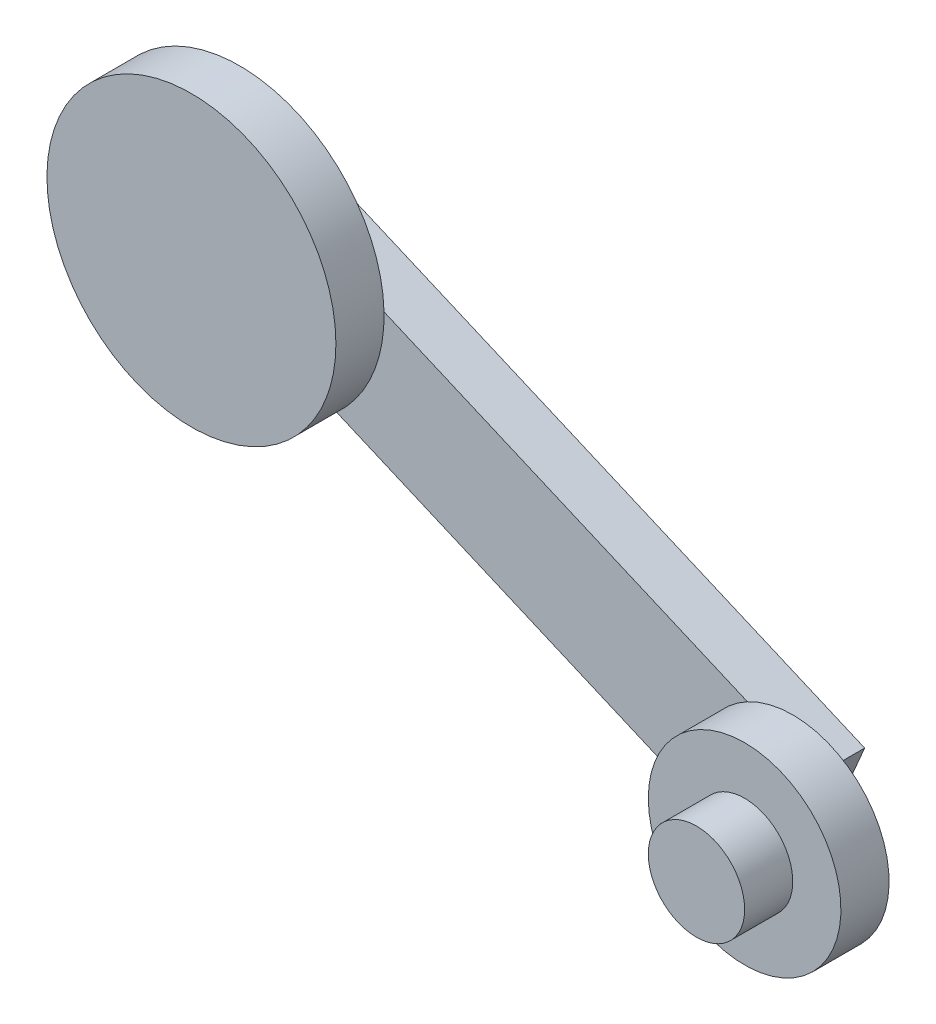
SolidWorks part; units mm, degrees
ref_plane "Front Plane" through (0, 0, 0) normal (0, 0, 1) x (1, 0, 0)
ref_plane "Top Plane" through (0, 0, 0) normal (0, 1, 0) x (1, 0, 0)
ref_plane "Right Plane" through (0, 0, 0) normal (1, 0, 0) x (0, 0, -1)
sketch "Sketch1" plane through (0, 0, 0) normal (0, 0, 1) x (1, 0, 0)
  circle A0 centre (0, 0) radius 2
extrude "Boss-Extrude1" add sketch "Sketch1" along normal blind 2
sketch "Sketch2" plane through (0, 0, 0) normal (0, 0, -1) x (-1, 0, 0)
  circle A0 centre (0, 0) radius 4
extrude "Boss-Extrude2" add sketch "Sketch2" along normal blind 2
sketch "Sketch3" plane through (0, 0, -2) normal (0, 0, -1) x (-1, 0, 0)
  line L0 (21.9881, 12.1563) -> (-0.9859, 2.2974)
  line L1 (21.9881, 12.1563) -> (23.9598, 7.5615)
  line L2 (-0.9859, 2.2974) -> (0.9859, -2.2974)
  line L3 (23.9598, 7.5615) -> (0.9859, -2.2974)
  line L4 (21.9881, 12.1563) -> (0.9859, -2.2974) construction
  line L5 (-0.9859, 2.2974) -> (23.9598, 7.5615) construction
  point P1 (11.487, 4.9294)
  point P2 (0, 0)
  dimension "D1" = 5
  dimension "D2" = 25
extrude "Boss-Extrude3" add sketch "Sketch3" along normal blind 2
sketch "Sketch4" plane through (0, 0, -2) normal (0, 0, 1) x (1, 0, 0)
  line L0 (-23.9598, 7.5615) -> (-21.9881, 12.1563) construction
  circle A0 centre (-22.9739, 9.8589) radius 6
extrude "Boss-Extrude4" add sketch "Sketch4" along normal blind 2
